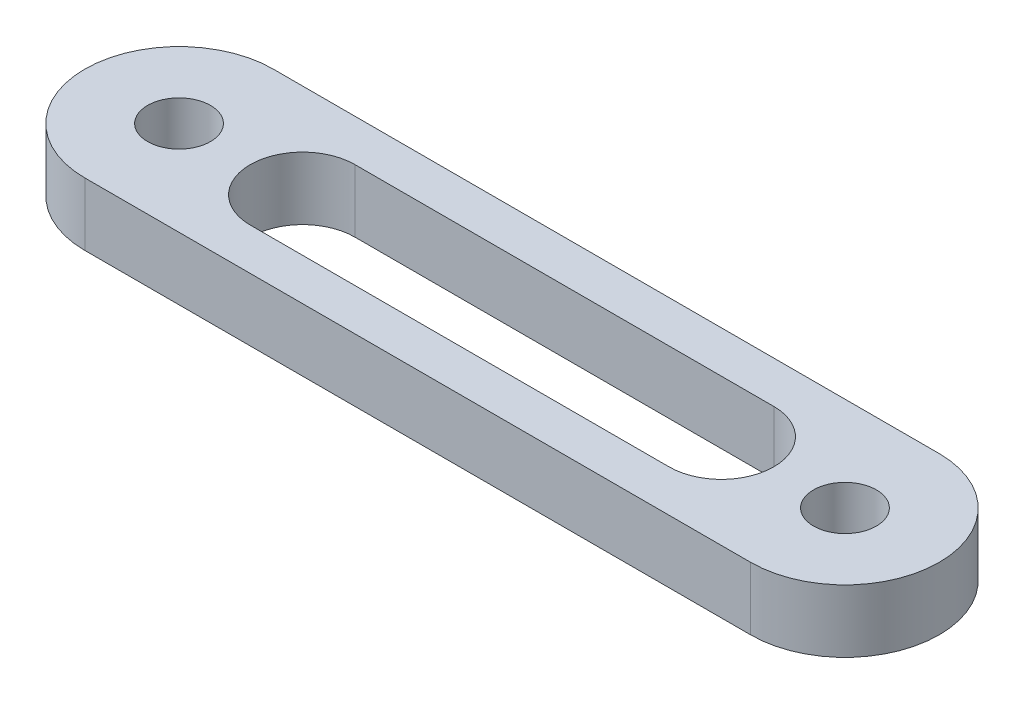
SolidWorks part; units mm, degrees
material "Thornel Mat VMA"
ref_plane "前视基准面" through (0, 0, 0) normal (0, 0, 1) x (1, 0, 0)
ref_plane "上视基准面" through (0, 0, 0) normal (0, 1, 0) x (1, 0, 0)
ref_plane "右视基准面" through (0, 0, 0) normal (1, 0, 0) x (0, 0, -1)
other "Configuration Table"
sketch "草图1" plane through (0, 0, 0) normal (0, 1, 0) x (1, 0, 0)
  line L0 (15.9, 0) -> (-15.9, 0) construction
  line L1 (-15.9, 4.5) -> (15.9, 4.5)
  line L2 (15.9, -4.5) -> (-15.9, -4.5)
  circle A0 centre (-15.9, 0) radius 1.5
  circle A1 centre (15.9, 0) radius 1.5
  circle A2 centre (-15.9, 0) radius 4.5
  circle A3 centre (15.9, 0) radius 4.5
  point P4 (0, 0)
  dimension "D2" = 3
  dimension "D1" = 31.8
  dimension "D3" = 3
extrude "凸台-拉伸1" add sketch "草图1" along normal blind 3
sketch "草图2" plane through (0, 3, 0) normal (0, 1, 0) x (1, 0, 0)
  line L0 (-10, 0) -> (10, 0) construction
  line L1 (-10, 2.5) -> (10, 2.5)
  line L2 (-10, -2.5) -> (10, -2.5)
  line L3 (-15.9, 4.5) -> (15.9, 4.5) construction
  arc A0 (-10, 2.5) -> (-10, -2.5) centre (-10, 0) ccw
  arc A1 (10, -2.5) -> (10, 2.5) centre (10, 0) ccw
  point P2 (0, 0)
  dimension "D1" = 20
  dimension "D2" = 2
extrude "切除-拉伸1" cut sketch "草图2" against normal through all
